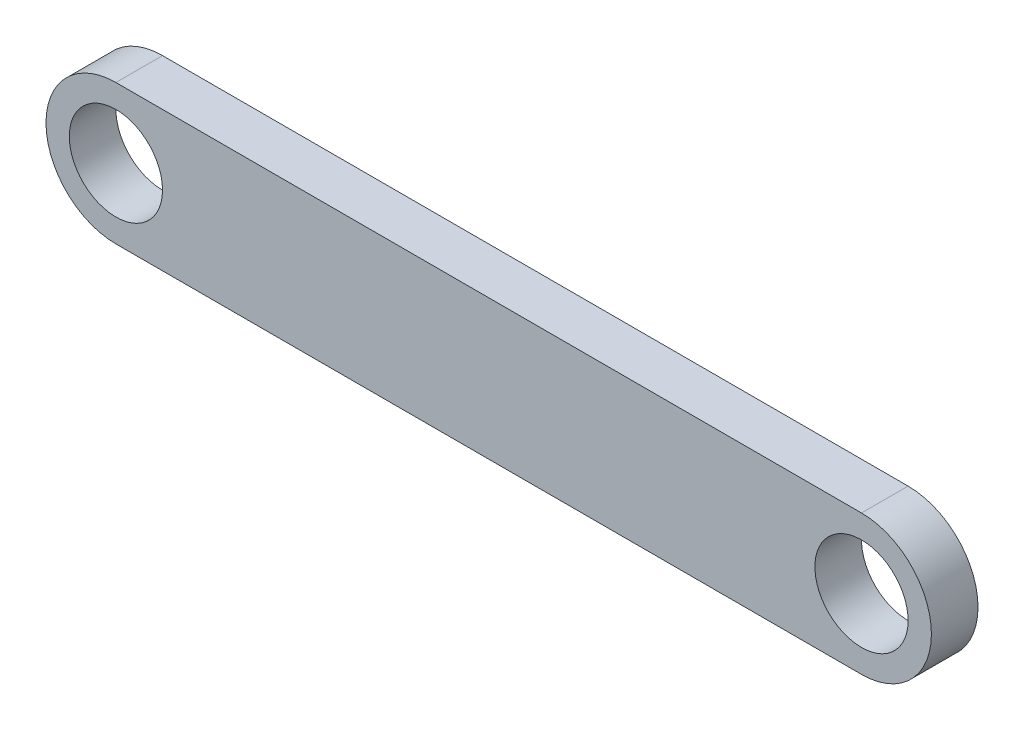
SolidWorks part; units mm, degrees
ref_plane "Спереди" through (0, 0, 0) normal (0, 0, 1) x (1, 0, 0)
ref_plane "Сверху" through (0, 0, 0) normal (0, 1, 0) x (1, 0, 0)
ref_plane "Справа" through (0, 0, 0) normal (1, 0, 0) x (0, 0, -1)
other "Configuration Table"
sketch "Эскиз1" plane through (0, 0, 0) normal (0, 0, 1) x (1, 0, 0)
  line L0 (0, 0) -> (160, 0) construction
  line L1 (0, 15) -> (160, 15)
  line L2 (0, -15) -> (160, -15)
  arc A0 (0, 15) -> (0, -15) centre (0, 0) ccw
  arc A1 (160, -15) -> (160, 15) centre (160, 0) ccw
  circle A2 centre (0, 0) radius 10
  circle A3 centre (160, 0) radius 10
  point P3 (80, 0)
  dimension "D1" = 160
  dimension "D2" = 30
extrude "Бобышка-Вытянуть1" add sketch "Эскиз1" along normal blind 10
